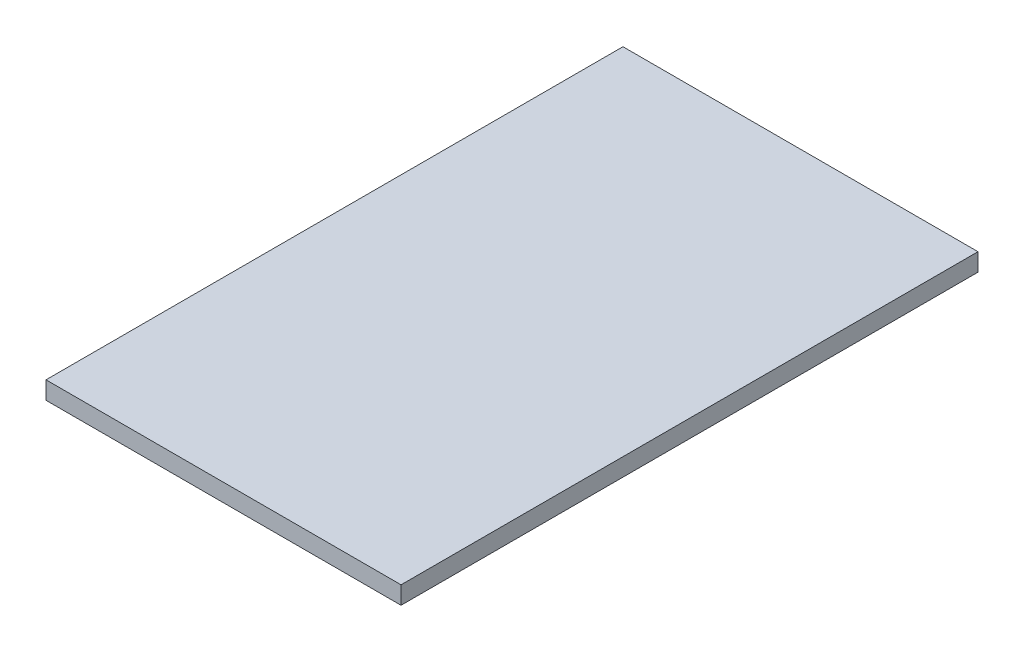
SolidWorks part; units mm, degrees
material "1060 Alloy"
ref_plane "Front Plane" through (0, 0, 0) normal (0, 0, 1) x (1, 0, 0)
ref_plane "Top Plane" through (0, 0, 0) normal (0, 1, 0) x (1, 0, 0)
ref_plane "Right Plane" through (0, 0, 0) normal (1, 0, 0) x (0, 0, -1)
sketch "Sketch1" plane through (0, 0, 0) normal (0, 1, 0) x (1, 0, 0)
  line L1 (-29.7873, -16.3945) -> (10.8527, -16.3945)
  line L2 (-29.7873, -16.3945) -> (-29.7873, 49.6455)
  line L3 (-29.7873, 49.6455) -> (10.8527, 49.6455)
  line L4 (10.8527, -16.3945) -> (10.8527, 49.6455)
  dimension "D1" = 40.64
  dimension "D2" = 66.04
extrude "Boss-Extrude1" add sketch "Sketch1" along normal blind 2.032
